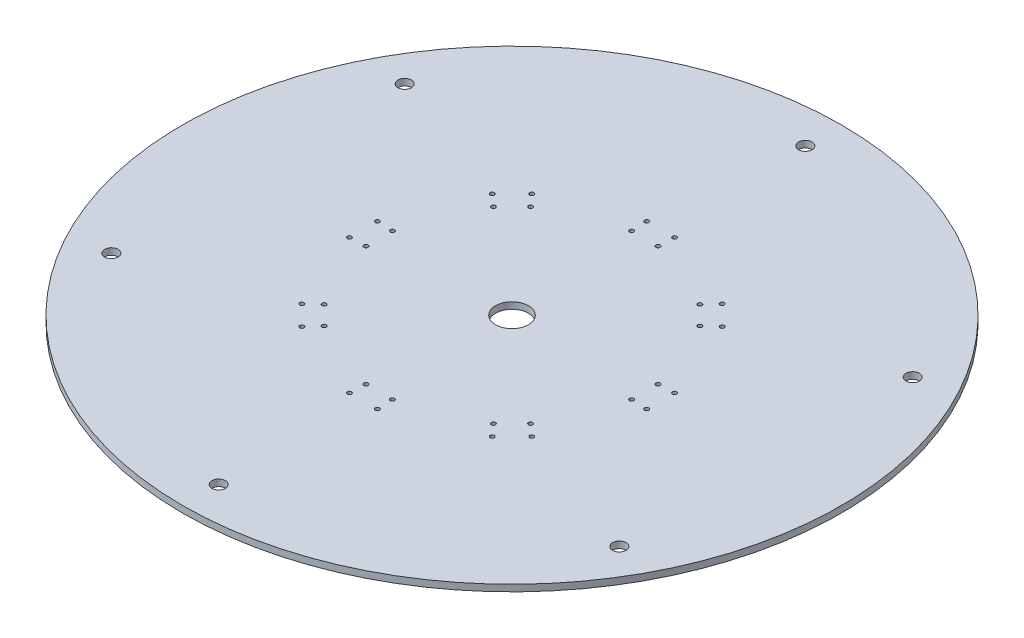
SolidWorks part; units mm, degrees
material "ABS PC"
ref_plane "Front Plane" through (0, 0, 0) normal (0, 0, 1) x (1, 0, 0)
ref_plane "Top Plane" through (0, 0, 0) normal (0, 1, 0) x (1, 0, 0)
ref_plane "Right Plane" through (0, 0, 0) normal (1, 0, 0) x (0, 0, -1)
sketch "Sketch1" plane through (0, 0, 0) normal (0, 1, 0) x (1, 0, 0)
  line L1 (0, 222.5) -> (0, 0) construction
  circle A0 centre (0, 0) radius 250
  circle A126 centre (0, 222.5) radius 5.1
  circle A127 centre (192.6907, 111.25) radius 5.1
  circle A128 centre (192.6907, -111.25) radius 5.1
  circle A129 centre (0, -222.5) radius 5.1
  circle A130 centre (-192.6907, -111.25) radius 5.1
  circle A131 centre (-192.6907, 111.25) radius 5.1
  circle A132 centre (0, 0) radius 222.5 construction
  circle A139 centre (0, 0) radius 101.25 construction
  circle A170 centre (0, 0) radius 12.5
  circle A173 centre (-10, 100.755) radius 1.6
  circle A174 centre (10, 100.755) radius 1.6
  circle A175 centre (0, 0) radius 113.233 construction
  circle A176 centre (-10.575, 112.7381) radius 1.6
  circle A177 centre (10.575, 112.7381) radius 1.6
  circle A178 centre (72.2402, 87.1955) radius 1.6
  circle A179 centre (87.1955, 72.2402) radius 1.6
  circle A180 centre (78.3156, 64.1734) radius 1.6
  circle A181 centre (64.1734, 78.3156) radius 1.6
  circle A182 centre (112.7381, 10.575) radius 1.6
  circle A183 centre (112.7381, -10.575) radius 1.6
  circle A184 centre (100.755, -10) radius 1.6
  circle A185 centre (100.755, 10) radius 1.6
  circle A186 centre (87.1955, -72.2402) radius 1.6
  circle A187 centre (72.2402, -87.1955) radius 1.6
  circle A188 centre (64.1734, -78.3156) radius 1.6
  circle A189 centre (78.3156, -64.1734) radius 1.6
  circle A190 centre (10.575, -112.7381) radius 1.6
  circle A191 centre (-10.575, -112.7381) radius 1.6
  circle A192 centre (-10, -100.755) radius 1.6
  circle A193 centre (10, -100.755) radius 1.6
  circle A194 centre (-72.2402, -87.1955) radius 1.6
  circle A195 centre (-87.1955, -72.2402) radius 1.6
  circle A196 centre (-78.3156, -64.1734) radius 1.6
  circle A197 centre (-64.1734, -78.3156) radius 1.6
  circle A198 centre (-112.7381, -10.575) radius 1.6
  circle A199 centre (-112.7381, 10.575) radius 1.6
  circle A200 centre (-100.755, 10) radius 1.6
  circle A201 centre (-100.755, -10) radius 1.6
  circle A202 centre (-87.1955, 72.2402) radius 1.6
  circle A203 centre (-72.2402, 87.1955) radius 1.6
  circle A204 centre (-64.1734, 78.3156) radius 1.6
  circle A205 centre (-78.3156, 64.1734) radius 1.6
  point P73 (0, 0)
  point P74 (0, 0)
  dimension "D2" = 222.5
  dimension "D4" = 445
  dimension "D5" = 202.5
  dimension "D7" = 25
  dimension "D8" = 20
  dimension "D9" = 3.2
  dimension "D10" = 21.15
  dimension "D11" = 3.2
  dimension "D14" = 10.2
  dimension "D3" = 500
  dimension "D6" = 226.466
  dimension "D15" = 6
extrude "Boss-Extrude1" add sketch "Sketch1" along normal mid plane 5
